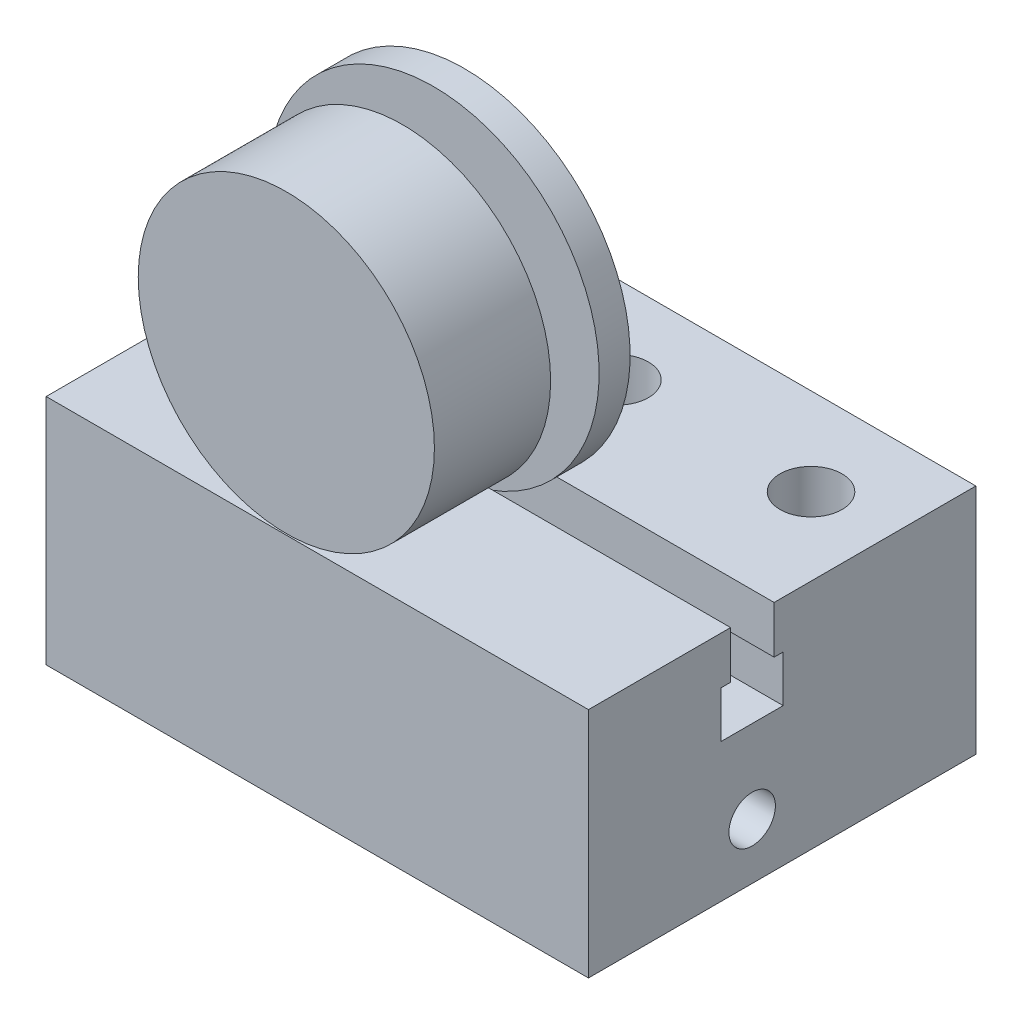
SolidWorks part; units mm, degrees
ref_plane "Front Plane" through (0, 0, 0) normal (0, 0, 1) x (1, 0, 0)
ref_plane "Top Plane" through (0, 0, 0) normal (0, 1, 0) x (1, 0, 0)
ref_plane "Right Plane" through (0, 0, 0) normal (1, 0, 0) x (0, 0, -1)
sketch "Sketch1" plane through (0, 0, 0) normal (0, 1, 0) x (1, 0, 0)
  line L1 (10.255, 44.7419) -> (80.255, 44.7419)
  line L2 (10.255, 44.7419) -> (10.255, -5.2581)
  line L3 (10.255, -5.2581) -> (80.255, -5.2581)
  line L4 (80.255, 44.7419) -> (80.255, -5.2581)
  circle A0 centre (45.255, 33.4759) radius 4
  circle A1 centre (70.255, 33.4668) radius 4
  circle A2 centre (20.255, 33.4678) radius 4
  dimension "D3" = 25
  dimension "D1" = 70
  dimension "D2" = 50
  dimension "D4" = 25
extrude "Boss-Extrude1" add sketch "Sketch1" along normal blind 30
sketch "Sketch2" plane through (10.255, 0, 0) normal (-1, 0, 0) x (0, 0, 1)
  line L3 (-19.8706, 17.881) -> (-11.8706, 17.881)
  line L4 (-11.8706, 23.881) -> (-11.8706, 17.881)
  line L9 (-19.8706, 17.881) -> (-19.8706, 23.881)
  line L10 (-19.8706, 23.881) -> (-18.7033, 23.881)
  line L11 (-18.7033, 23.881) -> (-18.7033, 30)
  line L13 (-13.0867, 30) -> (-13.0867, 23.881)
  line L14 (-13.0867, 23.881) -> (-11.8706, 23.881)
  line L15 (-44.7419, 30) -> (5.2581, 30) construction
  line L16 (-18.7033, 30) -> (-13.0867, 30)
  circle A0 centre (-15.8706, 7.1987) radius 3
  dimension "D1" = 6
  dimension "D2" = 8
extrude "Cut-Extrude1" cut sketch "Sketch2" against normal blind 71
sketch "Sketch6" plane through (0, 0, 5.2581) normal (0, 0, 1) x (1, 0, 0)
  circle A0 centre (41.255, 49.2849) radius 19.1151
extrude "Boss-Extrude3" add sketch "Sketch6" against normal blind 15 separate body
sketch "Sketch7" plane through (0, 0, -9.7419) normal (0, 0, -1) x (-1, 0, 0)
  circle A0 centre (-41.255, 49.2849) radius 2
extrude "Boss-Extrude4" add sketch "Sketch7" along normal blind 4
sketch "Sketch8" plane through (0, 0, -13.7419) normal (0, 0, -1) x (-1, 0, 0)
  circle A0 centre (-41.255, 49.2849) radius 21.3745
extrude "Boss-Extrude5" add sketch "Sketch8" along normal blind 4 contours A0
